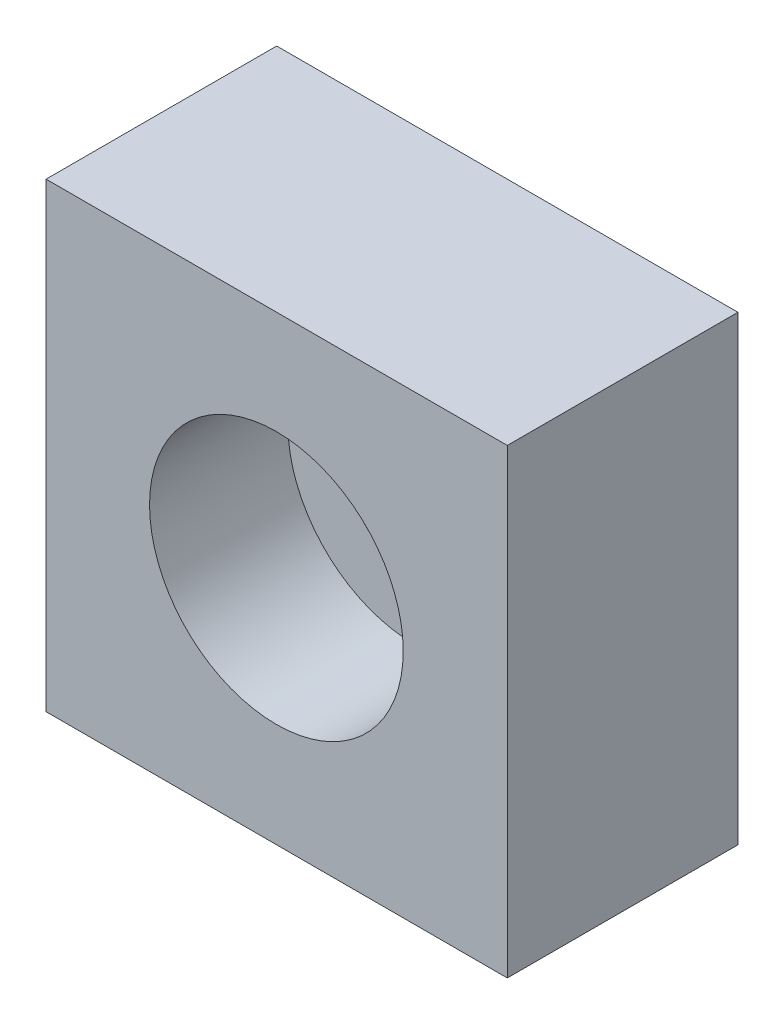
SolidWorks part; units mm, degrees
ref_plane "前视基准面" through (0, 0, 0) normal (0, 0, 1) x (1, 0, 0)
ref_plane "上视基准面" through (0, 0, 0) normal (0, 1, 0) x (1, 0, 0)
ref_plane "右视基准面" through (0, 0, 0) normal (1, 0, 0) x (0, 0, -1)
other "Configuration Table"
sketch "草图1" plane through (0, 0, 0) normal (0, 0, 1) x (1, 0, 0)
  line L1 (0, 0) -> (20, 0)
  line L2 (0, 0) -> (0, 20)
  line L3 (0, 20) -> (20, 20)
  line L4 (20, 0) -> (20, 20)
extrude "BaseBox" add sketch "草图1" along normal blind 10
hole_wizard "Hole_BlindCbore_thru_depth8" positions "草图3" profile "草图2" counterbore size "M6" standard "ISO"
sketch "草图3" plane through (0, 0, 10) normal (0, 0, 1) x (1, 0, 0)
  point P0 (9.9865, 10.0143)
sketch "草图2" plane through (9.9865, 10.0143, 10) normal (1, 0, 0) x (0, -1, 0)
  line L0 (0, 0) -> (0, 8)
  line L1 (0, 8) -> (3, 8)
  line L3 (3, 8) -> (3, 6)
  line L4 (3, 6) -> (5.5, 6)
  line L5 (5.5, 6) -> (5.5, 0)
  line L7 (5.5, 0) -> (0, 0)
  line L11 (0, -6.35) -> (0, 107.95) construction
  dimension "通孔孔直径" = 6
  dimension "通孔孔深度" = 8
  dimension "柱形沉头孔直径" = 11
  dimension "柱形沉头孔深度" = 6
